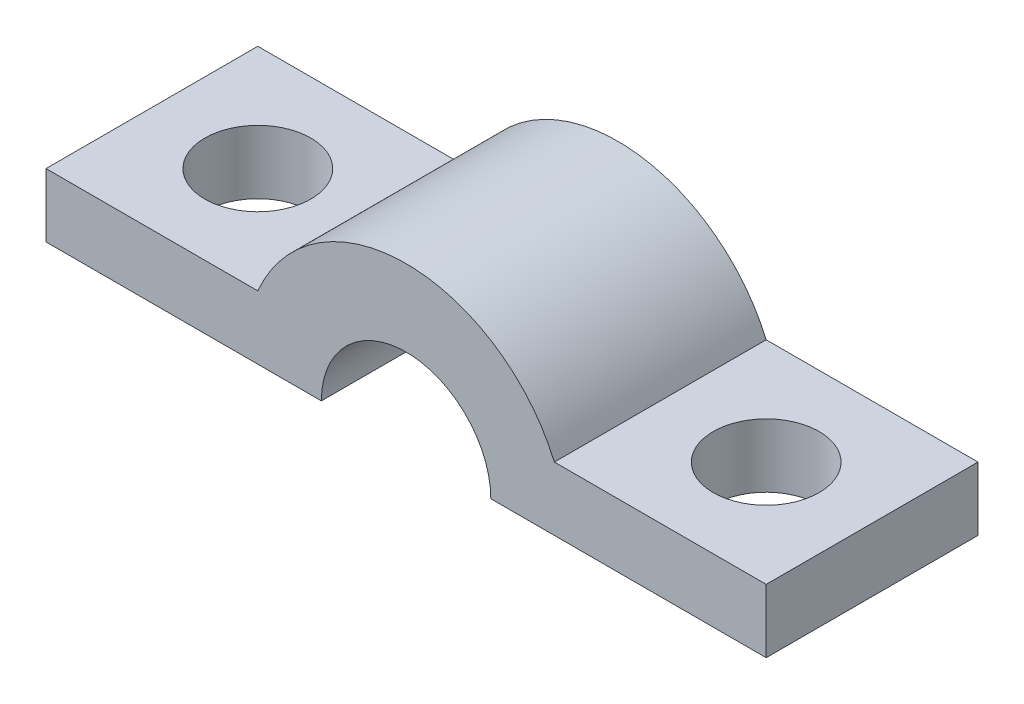
SolidWorks part; units mm, degrees
ref_plane "Front Plane" through (0, 0, 0) normal (0, 0, 1) x (1, 0, 0)
ref_plane "Top Plane" through (0, 0, 0) normal (0, 1, 0) x (1, 0, 0)
ref_plane "Right Plane" through (0, 0, 0) normal (1, 0, 0) x (0, 0, -1)
sketch "Sketch1" plane through (0, 0, 0) normal (0, 0, 1) x (1, 0, 0)
  line L0 (-3.81, 3.81) -> (-16.51, 3.81)
  line L1 (-16.51, 3.81) -> (-16.51, 0)
  line L2 (-16.51, 0) -> (0, 0)
  line L3 (5.08, 0) -> (5.08, 9.672) construction
  line L4 (26.67, 0) -> (10.16, 0)
  line L5 (26.67, 3.81) -> (26.67, 0)
  line L6 (13.97, 3.81) -> (26.67, 3.81)
  arc A0 (0, 0) -> (10.16, 0) centre (5.08, 0) cw
  arc A1 (-3.81, 3.81) -> (13.97, 3.81) centre (5.08, 0) cw
  point P5 (6.8359, 11.3071)
  point P9 (5.08, 9.672)
  point P13 (31.1013, 4.1205)
  point P14 (-1.6027, 3.81)
  point P15 (15.0134, 0)
  point P16 (7.5067, -0.2841)
  point P17 (33.3566, 3.81)
  point P18 (16.51, 3.81)
  point P19 (6.35, 0)
  point P20 (0, 0)
  dimension "D1" = 12.7
  dimension "D2" = 3.81
  dimension "D3" = 3.81
  dimension "D4" = 10.16
extrude "Boss-Extrude1" add sketch "Sketch1" along normal blind 12.7
sketch "Sketch2" plane through (0, 3.81, 0) normal (0, 1, 0) x (1, 0, 0)
  line L0 (-10.16, 0) -> (-10.16, -12.7) construction
  line L1 (-3.81, 0) -> (-16.51, 0) construction
  line L2 (-3.81, -12.7) -> (-16.51, -12.7) construction
  line L3 (-16.51, -6.35) -> (-3.81, -6.35) construction
  line L4 (-16.51, -12.7) -> (-16.51, 0) construction
  line L5 (-3.81, -12.7) -> (-3.81, 0) construction
  line L6 (5.08, 0) -> (5.08, -12.7) construction
  line L7 (13.97, 0) -> (-3.81, 0) construction
  line L8 (-3.81, -12.7) -> (13.97, -12.7) construction
  circle A0 centre (-10.16, -6.35) radius 3.175
  circle A1 centre (20.32, -6.35) radius 3.175
  point P15 (-10.16, -6.35)
  dimension "D1" = 6.35
extrude "Cut-Extrude1" cut sketch "Sketch2" against normal through all
